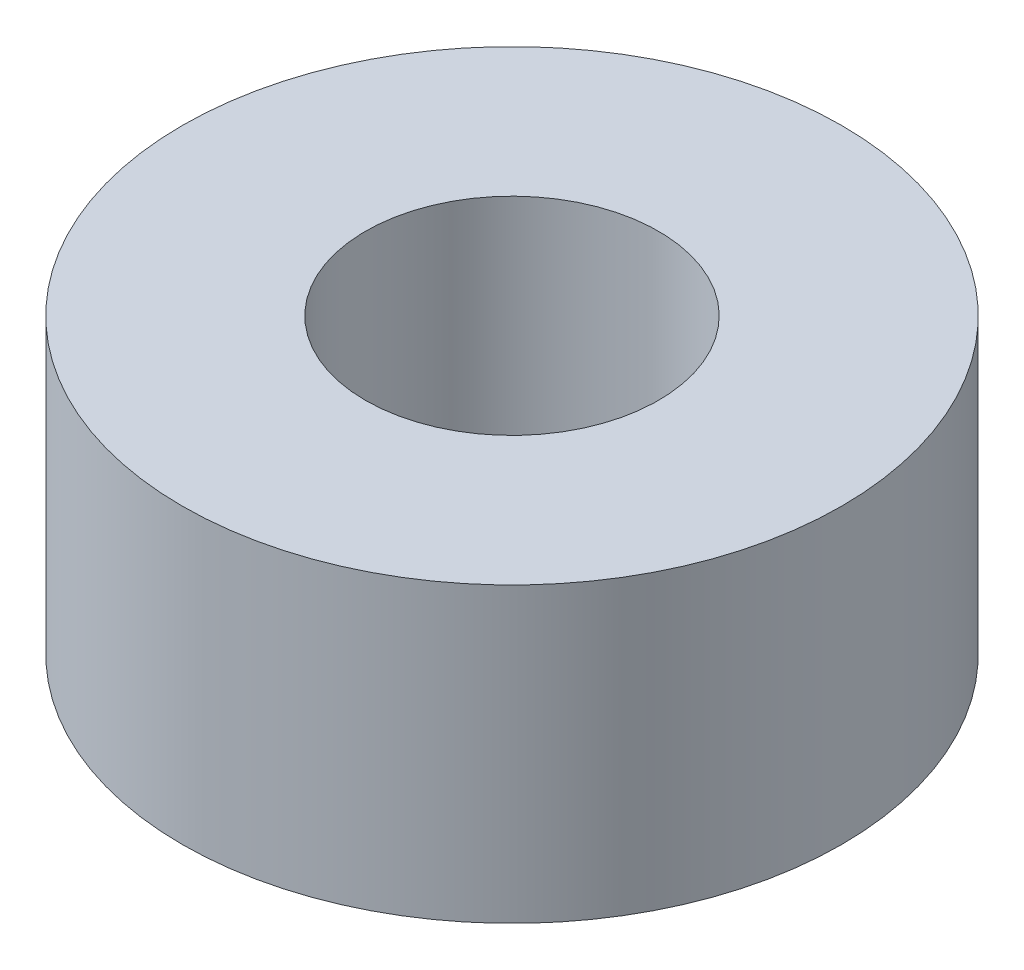
SolidWorks part; units mm, degrees
material "Brass"
ref_plane "Front Plane" through (0, 0, 0) normal (0, 0, 1) x (1, 0, 0)
ref_plane "Top Plane" through (0, 0, 0) normal (0, 1, 0) x (1, 0, 0)
ref_plane "Right Plane" through (0, 0, 0) normal (1, 0, 0) x (0, 0, -1)
sketch "Sketch1" plane through (0, 0, 0) normal (0, 1, 0) x (1, 0, 0)
  circle A0 centre (0, 0) radius 4.5
  circle A1 centre (0, 0) radius 2
  dimension "D1" = 9
  dimension "D2" = 4
extrude "Boss-Extrude1" add sketch "Sketch1" along normal blind 4
